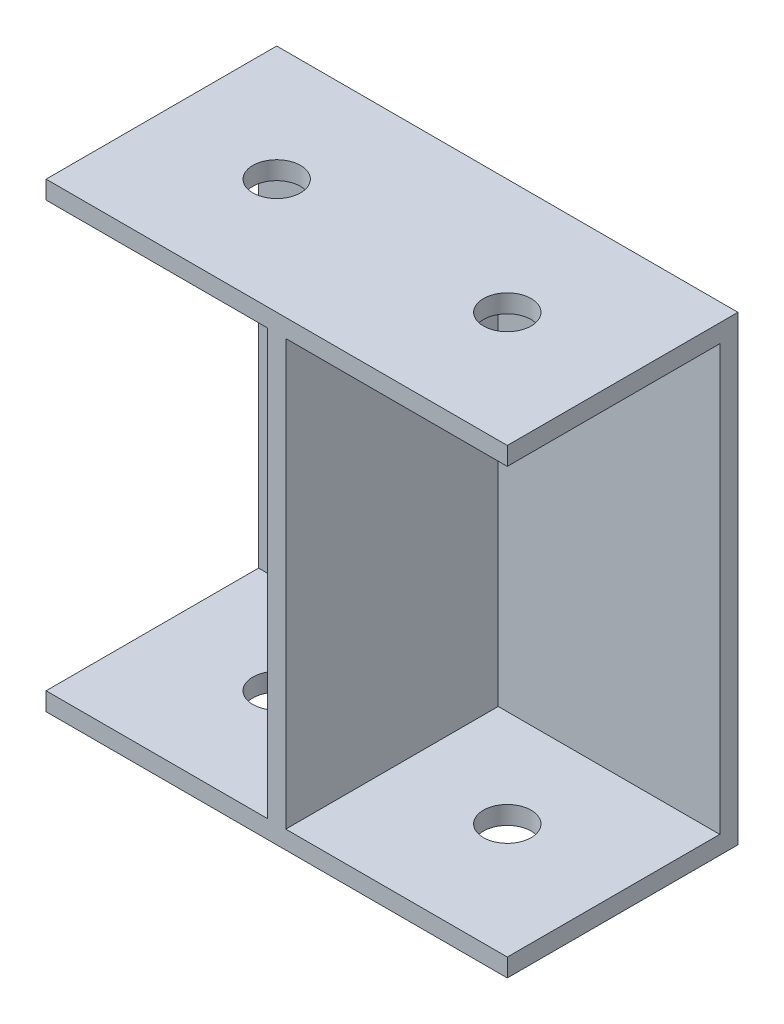
SolidWorks part; units mm, degrees
ref_plane "Front Plane" through (0, 0, 0) normal (0, 0, 1) x (1, 0, 0)
ref_plane "Top Plane" through (0, 0, 0) normal (0, 1, 0) x (1, 0, 0)
ref_plane "Right Plane" through (0, 0, 0) normal (1, 0, 0) x (0, 0, -1)
sketch "Sketch1" plane through (0, 0, 0) normal (0, 0, 1) x (1, 0, 0)
  line L1 (-38.1, -38.1) -> (38.1, -38.1)
  line L2 (-38.1, -38.1) -> (-38.1, 38.1)
  line L3 (-38.1, 38.1) -> (38.1, 38.1)
  line L4 (38.1, -38.1) -> (38.1, 38.1)
  line L5 (-38.1, -38.1) -> (38.1, 38.1) construction
  line L6 (-38.1, 38.1) -> (38.1, -38.1) construction
  point P0 (38.1, 38.1)
  point P1 (0, 0)
extrude "Boss-Extrude1" add sketch "Sketch1" along normal blind 38.1
sketch3d "3DSketch2" plane through (0, 0, 0) normal (0, 0, 1) x (1, 0, 0)
sketch "Sketch3" plane through (0, 0, 38.1) normal (0, 0, 1) x (1, 0, 0)
  line L1 (1.5, -35.1) -> (40.9634, -35.1)
  line L2 (1.5, -35.1) -> (1.5, 35.1)
  line L3 (1.5, 35.1) -> (40.9634, 35.1)
  line L4 (40.9634, -35.1) -> (40.9634, 35.1)
  line L5 (-40.8483, -35.1) -> (-40.8483, 35.1)
  line L6 (-1.5, 35.1) -> (-40.8483, 35.1)
  line L7 (-1.5, -35.1) -> (-1.5, 35.1)
  line L8 (-1.5, -35.1) -> (-40.8483, -35.1)
  point P0 (40.9634, 35.1)
  point P1 (1.5, -35.1)
  point P12 (35.1, 35.1)
extrude "Cut-Extrude1" cut sketch "Sketch3" against normal blind 35.1
sketch "Sketch4" plane through (0, 0, 0) normal (0, 1, 0) x (1, 0, 0)
  line L0 (0, 0) -> (0, -23.5943) construction
  circle A0 centre (19.05, -19.05) radius 3.937
  circle A1 centre (-19.05, -19.05) radius 3.937
  point P0 (19.05, -19.05)
extrude "Cut-Extrude2" cut sketch "Sketch4" against normal mid plane 76.2
